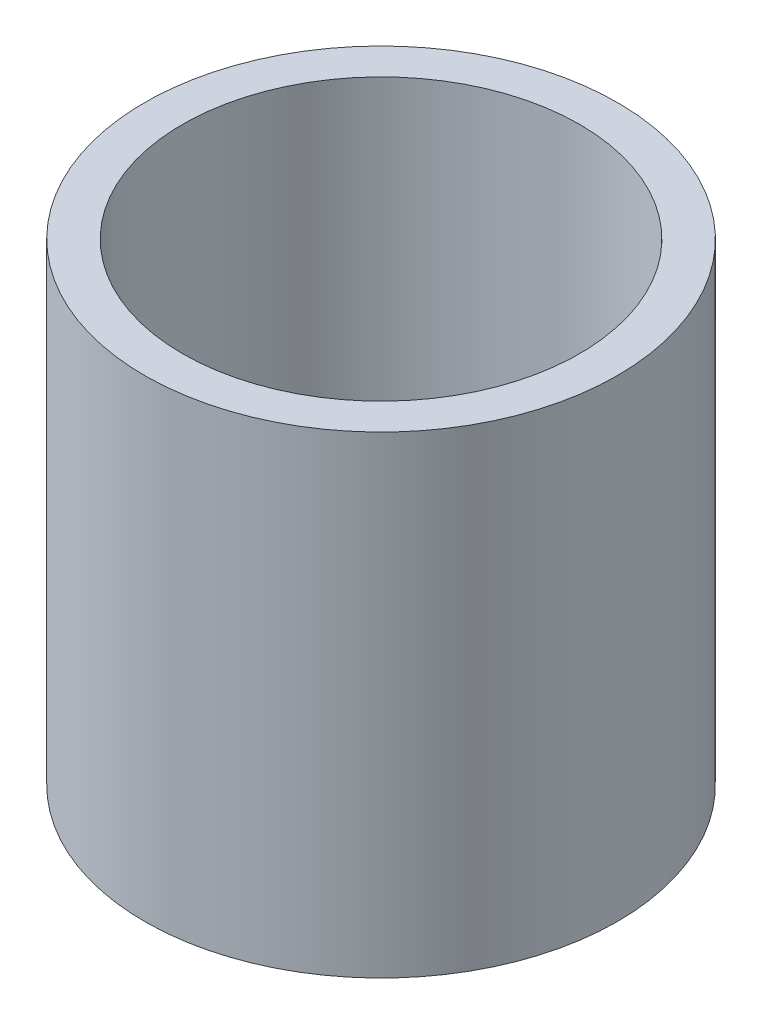
SolidWorks part; units mm, degrees
ref_plane "Front Plane" through (0, 0, 0) normal (0, 0, 1) x (1, 0, 0)
ref_plane "Top Plane" through (0, 0, 0) normal (0, 1, 0) x (1, 0, 0)
ref_plane "Right Plane" through (0, 0, 0) normal (1, 0, 0) x (0, 0, -1)
sketch "Sketch3" plane through (0, 0, 0) normal (0, 1, 0) x (1, 0, 0)
  circle A0 centre (0, 0) radius 21
extrude "Extrude-Thin1" add sketch "Sketch3" along normal blind 50 thin
sketch "Sketch4" plane through (0, 0, 0) normal (0, 1, 0) x (1, 0, 0)
  circle A0 centre (0, 0) radius 21
extrude "Boss-Extrude1" add sketch "Sketch4" along normal blind 4
